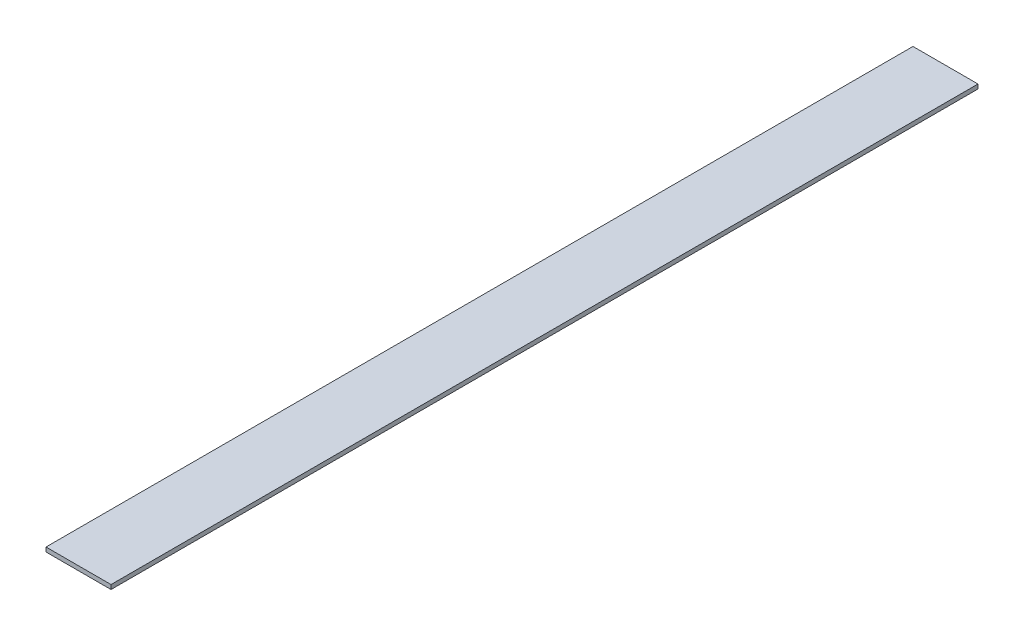
SolidWorks part; units mm, degrees
ref_plane "Front" through (0, 0, 0) normal (0, 0, 1) x (1, 0, 0)
ref_plane "Top" through (0, 0, 0) normal (0, 1, 0) x (1, 0, 0)
ref_plane "Right" through (0, 0, 0) normal (1, 0, 0) x (0, 0, -1)
sketch "Sketch1" plane through (0, 0, 0) normal (0, 1, 0) x (1, 0, 0)
  line L1 (0, 0) -> (15, 0)
  line L2 (0, 0) -> (0, 200)
  line L3 (0, 200) -> (15, 200)
  line L4 (15, 0) -> (15, 200)
  dimension "D1" = 200
  dimension "D2" = 15
extrude "Boss-Extrude1" add sketch "Sketch1" along normal blind 1
